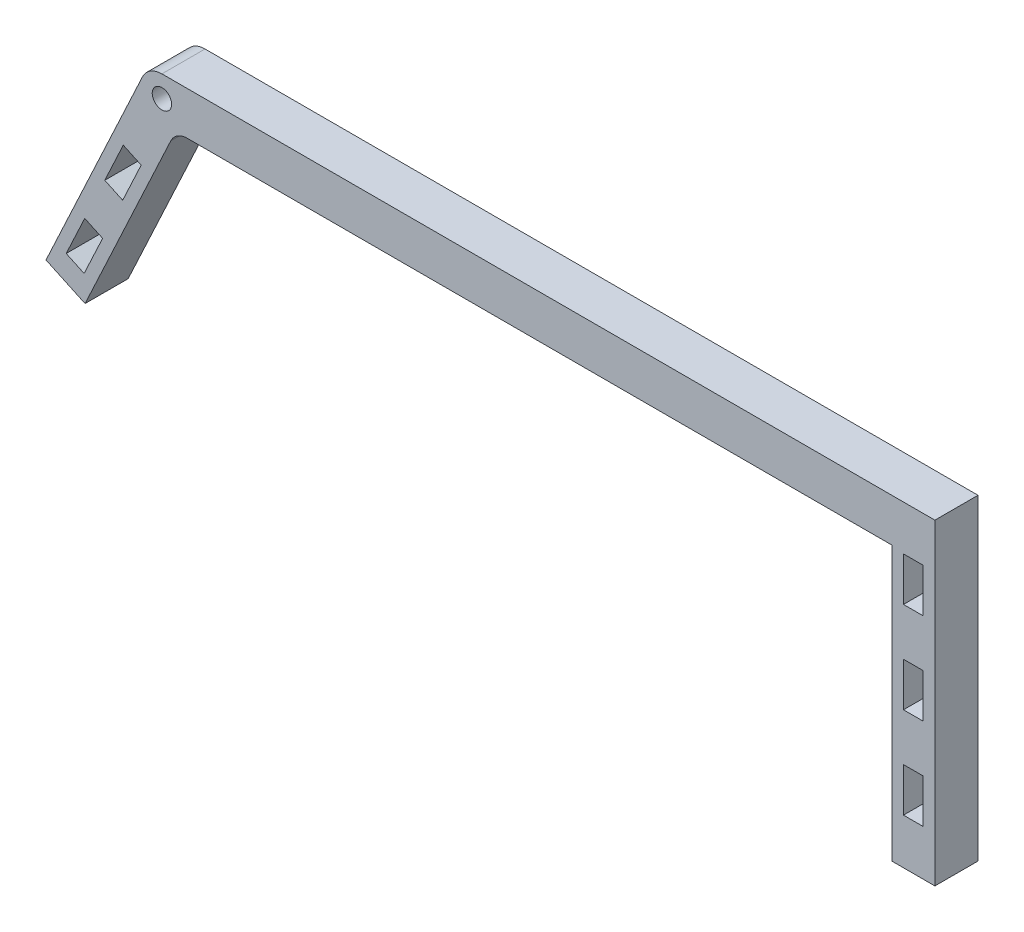
SolidWorks part; units mm, degrees
ref_plane "Front Plane" through (0, 0, 0) normal (0, 0, 1) x (1, 0, 0)
ref_plane "Top Plane" through (0, 0, 0) normal (0, 1, 0) x (1, 0, 0)
ref_plane "Right Plane" through (0, 0, 0) normal (1, 0, 0) x (0, 0, -1)
sketch "Sketch1" plane through (0, 0, 0) normal (0, 0, 1) x (1, 0, 0)
  line L0 (-50.3888, -3) -> (-62.9992, -30.0431)
  line L1 (-50.3888, -3) -> (55.3, -3)
  line L2 (-55.3, 0.6651) -> (-55.3, 3) construction
  line L3 (-52.3, 3) -> (55.3, 3)
  line L5 (-55.3, -3) -> (55.3, 3) construction
  line L6 (-55.3, 3) -> (55.3, -3) construction
  line L8 (55.3, 3) -> (55.3, -41.1)
  line L9 (55.3, -41.1) -> (49.3, -41.1)
  line L10 (49.3, 3) -> (49.3, -41.1)
  line L11 (-55.3, 0.6651) -> (-68.4371, -27.5074)
  line L12 (-68.4371, -27.5074) -> (-62.9992, -30.0431)
  line L13 (-55.3, 3) -> (-52.3, 3) construction
  line L14 (-55.3, -3) -> (-52.3, -3) construction
  line L15 (-52.3, -3) -> (-50.3888, -3) construction
  line L16 (-55.3, -3) -> (-55.3, 0) construction
  line L17 (-55.3, 0) -> (-55.3, 0.6651) construction
  line L18 (-55.3, 0.6651) -> (-55.0189, 1.2679)
  circle A0 centre (-52.3, 0) radius 1.35
  arc A2 (-52.3, 3) -> (-55.0189, 1.2679) centre (-52.3, 0) ccw
  arc A3 (-55.0189, 1.2679) -> (-55.3, 0) centre (-52.3, 0) ccw construction
  arc A4 (-55.3, 0) -> (-53.1318, -2.8824) centre (-52.3, 0) ccw construction
  arc A5 (-53.1318, -2.8824) -> (-52.3, -3) centre (-52.3, 0) ccw construction
  arc A6 (-52.3, -3) -> (-51.1613, -2.7755) centre (-52.3, 0) ccw construction
  arc A7 (-51.1613, -2.7755) -> (-53.1318, 2.8824) centre (-52.3, 0) ccw construction
  arc A8 (-53.1318, 2.8824) -> (-52.3, 3) centre (-52.3, 0) ccw construction
  point P0 (0, 0)
  dimension "D5" = 2.7
  dimension "D1" = 6
  dimension "D2" = 101.6
  dimension "D3" = 44.1
  dimension "D4" = 6
  dimension "D6" = 115
  dimension "D7" = 3
  dimension "D8" = 3
  dimension "D9" = 6
  dimension "D10" = 31.75
extrude "Boss-Extrude1" add sketch "Sketch1" along normal mid plane 6
fillet "Fillet1" radius 2.54 1 edges at (-50.3888, -3, 0)
sketch "Sketch2" plane through (0, 0, 3) normal (0, 0, 1) x (1, 0, 0)
  line L0 (-63.0462, -19.7918) -> (-65.6225, -25.3166)
  line L1 (-63.0462, -19.7918) -> (-60.5539, -20.954)
  line L2 (-65.6225, -25.3166) -> (-63.1301, -26.4788)
  line L3 (-60.5539, -20.954) -> (-63.1301, -26.4788)
  line L4 (-68.4371, -27.5074) -> (-55.0189, 1.2679) construction
  line L5 (-68.4371, -27.5074) -> (-62.9992, -30.0431) construction
  line L6 (-51.0727, -4.4665) -> (-62.9992, -30.0431) construction
  point P10 (-64.3763, -25.8977)
  dimension "D1" = 2.75
  dimension "D2" = 6.096
  dimension "D3" = 3.175
  dimension "D4" = 3
extrude "Cut-Extrude1" cut sketch "Sketch2" against normal through all both and the other way through all
pattern_linear "LPattern1" count 2 spacing 12.7 along (0.4226, 0.9063, 0) of "Cut-Extrude1"
sketch "Sketch3" plane through (0, 0, 3) normal (0, 0, 1) x (1, 0, 0)
  line L0 (55.3, -41.1) -> (49.3, -41.1) construction
  line L1 (50.925, -28.654) -> (53.675, -28.654)
  line L2 (50.925, -28.654) -> (50.925, -34.75)
  line L3 (50.925, -34.75) -> (53.675, -34.75)
  line L4 (53.675, -28.654) -> (53.675, -34.75)
  line L5 (49.3, -3) -> (49.3, -41.1) construction
  point P6 (52.3, -34.75)
  dimension "D1" = 2.75
  dimension "D2" = 6.096
  dimension "D3" = 6.35
  dimension "D4" = 3
extrude "Cut-Extrude2" cut sketch "Sketch3" against normal through all both and the other way through all
pattern_linear "LPattern2" count 3 spacing 12.7 along (0, 1, 0) of "Cut-Extrude2"
